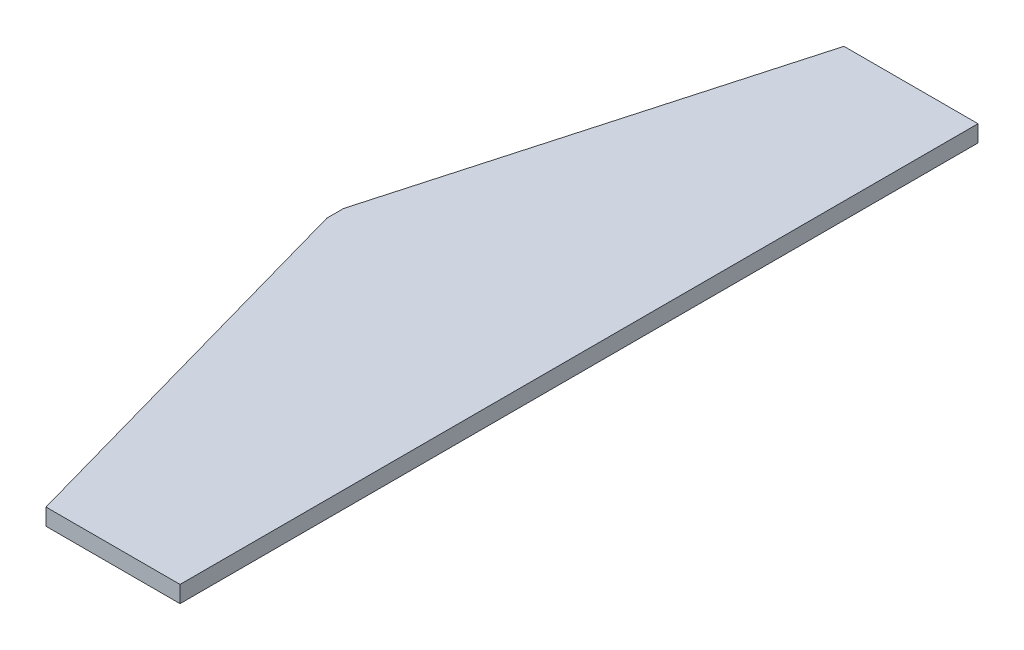
SolidWorks part; units mm, degrees
ref_plane "Front Plane" through (0, 0, 0) normal (0, 0, 1) x (1, 0, 0)
ref_plane "Top Plane" through (0, 0, 0) normal (0, 1, 0) x (1, 0, 0)
ref_plane "Right Plane" through (0, 0, 0) normal (1, 0, 0) x (0, 0, -1)
sketch "Sketch1" plane through (0, 0, 0) normal (0, 1, 0) x (1, 0, 0)
  line L1 (219, 0) -> (219, 350.9)
  line L2 (219, 350.9) -> (98.6, 350.9)
  line L3 (98.6, 350.9) -> (0, 0)
  line L4 (-18.1002, -7.5) -> (0, -7.5) construction
  line L5 (219, -365.9) -> (98.6, -365.9)
  line L6 (219, -15) -> (219, -365.9)
  line L8 (98.6, -365.9) -> (0, -15)
  line L9 (0, 0) -> (0, -15)
  line L10 (219, 0) -> (219, -15)
  line L11 (219, -7.5) -> (272.9736, -7.5) construction
  dimension "D1" = 219
  dimension "D2" = 350.9
  dimension "D3" = 120.4
extrude "Boss-Extrude1" add sketch "Sketch1" along normal blind 15
scale "Scale2" scale about centroid uniform scaling yes scale factor 0.6
